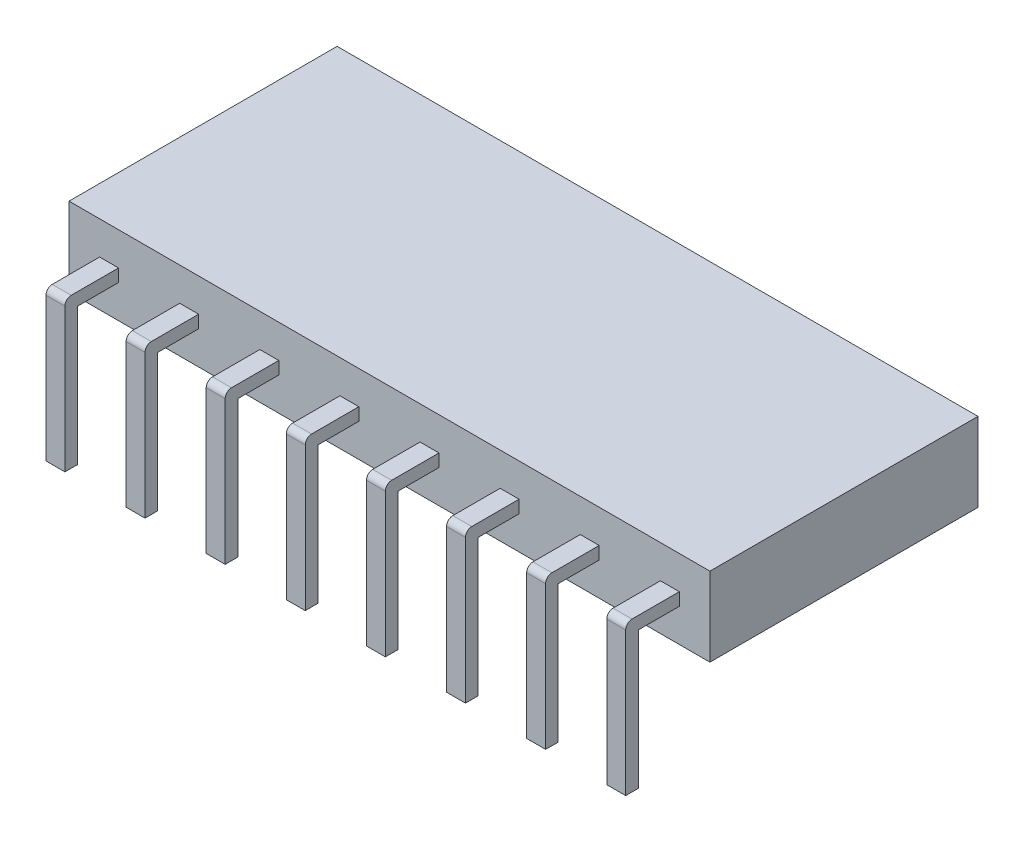
SolidWorks part; units mm, degrees
ref_plane "Front" through (0, 0, 0) normal (0, 0, 1) x (1, 0, 0)
ref_plane "Top" through (0, 0, 0) normal (0, 1, 0) x (1, 0, 0)
ref_plane "Right" through (0, 0, 0) normal (1, 0, 0) x (0, 0, -1)
sketch "Эскиз1" plane through (0, 0, 0) normal (0, 1, 0) x (1, 0, 0)
  line L1 (-10.16, 4.25) -> (10.16, 4.25)
  line L2 (-10.16, 4.25) -> (-10.16, -4.25)
  line L3 (-10.16, -4.25) -> (10.16, -4.25)
  line L4 (10.16, 4.25) -> (10.16, -4.25)
  line L5 (-10.16, 4.25) -> (10.16, -4.25) construction
  line L6 (-10.16, -4.25) -> (10.16, 4.25) construction
  point P0 (0, 0)
extrude "Бобышка-Вытянуть1" add sketch "Эскиз1" along normal blind 2.5
sketch "Эскиз2" plane through (0, 0, 4.25) normal (0, 0, 1) x (1, 0, 0)
  line L0 (-10.16, 1.25) -> (10.16, 1.25) construction
  line L1 (-10.16, 2.5) -> (-10.16, 0) construction
  line L2 (10.16, 2.5) -> (10.16, 0) construction
  line L3 (-6.65, 1.05) -> (-6.05, 1.05)
  line L4 (-9.19, 1.05) -> (-8.59, 1.05)
  line L5 (-9.19, 1.05) -> (-9.19, 1.45)
  line L6 (-9.19, 1.45) -> (-8.59, 1.45)
  line L7 (-8.59, 1.05) -> (-8.59, 1.45)
  line L8 (-9.19, 1.05) -> (-8.59, 1.45) construction
  line L9 (-9.19, 1.45) -> (-8.59, 1.05) construction
  line L10 (-6.65, 1.05) -> (-6.05, 1.45) construction
  line L11 (-6.65, 1.05) -> (-6.65, 1.45)
  line L12 (-6.65, 1.45) -> (-6.05, 1.45)
  line L13 (-6.65, 1.45) -> (-6.05, 1.05) construction
  line L14 (-6.05, 1.05) -> (-6.05, 1.45)
  line L15 (-4.11, 1.05) -> (-3.51, 1.05)
  line L16 (-4.11, 1.05) -> (-3.51, 1.45) construction
  line L17 (-4.11, 1.05) -> (-4.11, 1.45)
  line L18 (-4.11, 1.45) -> (-3.51, 1.45)
  line L19 (-4.11, 1.45) -> (-3.51, 1.05) construction
  line L20 (-3.51, 1.05) -> (-3.51, 1.45)
  line L21 (-1.57, 1.05) -> (-0.97, 1.05)
  line L22 (-1.57, 1.05) -> (-0.97, 1.45) construction
  line L23 (-1.57, 1.05) -> (-1.57, 1.45)
  line L24 (-1.57, 1.45) -> (-0.97, 1.45)
  line L25 (-1.57, 1.45) -> (-0.97, 1.05) construction
  line L26 (-0.97, 1.05) -> (-0.97, 1.45)
  line L27 (0.97, 1.05) -> (1.57, 1.05)
  line L28 (0.97, 1.05) -> (1.57, 1.45) construction
  line L29 (0.97, 1.05) -> (0.97, 1.45)
  line L30 (0.97, 1.45) -> (1.57, 1.45)
  line L31 (0.97, 1.45) -> (1.57, 1.05) construction
  line L32 (1.57, 1.05) -> (1.57, 1.45)
  line L33 (3.51, 1.05) -> (4.11, 1.05)
  line L34 (3.51, 1.05) -> (4.11, 1.45) construction
  line L35 (3.51, 1.05) -> (3.51, 1.45)
  line L36 (3.51, 1.45) -> (4.11, 1.45)
  line L37 (3.51, 1.45) -> (4.11, 1.05) construction
  line L38 (4.11, 1.05) -> (4.11, 1.45)
  line L39 (6.05, 1.05) -> (6.65, 1.05)
  line L40 (6.05, 1.05) -> (6.65, 1.45) construction
  line L41 (6.05, 1.05) -> (6.05, 1.45)
  line L42 (6.05, 1.45) -> (6.65, 1.45)
  line L43 (6.05, 1.45) -> (6.65, 1.05) construction
  line L44 (6.65, 1.05) -> (6.65, 1.45)
  line L45 (8.59, 1.05) -> (9.19, 1.05)
  line L46 (8.59, 1.05) -> (9.19, 1.45) construction
  line L47 (8.59, 1.05) -> (8.59, 1.45)
  line L48 (8.59, 1.45) -> (9.19, 1.45)
  line L49 (8.59, 1.45) -> (9.19, 1.05) construction
  line L50 (9.19, 1.05) -> (9.19, 1.45)
  dimension "D1" = 8
extrude "Бобышка-Вытянуть2" add sketch "Эскиз2" along normal blind 1.7
sketch "Эскиз3" plane through (0, 1.05, 0) normal (0, -1, 0) x (1, 0, 0)
  line L0 (-8.59, 5.95) -> (-8.59, 4.25) construction
  line L1 (-9.19, 5.95) -> (-8.59, 5.95)
  line L2 (-9.19, 5.95) -> (-9.19, 5.55)
  line L3 (-9.19, 5.55) -> (-8.59, 5.55)
  line L4 (-8.59, 5.95) -> (-8.59, 5.55)
  line L5 (-6.65, 5.95) -> (-6.05, 5.95)
  line L6 (-6.65, 5.95) -> (-6.65, 5.55)
  line L7 (-6.65, 5.55) -> (-6.05, 5.55)
  line L8 (-6.05, 5.95) -> (-6.05, 5.55)
  line L9 (-4.11, 5.95) -> (-3.51, 5.95)
  line L10 (-4.11, 5.95) -> (-4.11, 5.55)
  line L11 (-4.11, 5.55) -> (-3.51, 5.55)
  line L12 (-3.51, 5.95) -> (-3.51, 5.55)
  line L13 (-1.57, 5.95) -> (-0.97, 5.95)
  line L14 (-1.57, 5.95) -> (-1.57, 5.55)
  line L15 (-1.57, 5.55) -> (-0.97, 5.55)
  line L16 (-0.97, 5.95) -> (-0.97, 5.55)
  line L17 (0.97, 5.95) -> (1.57, 5.95)
  line L18 (0.97, 5.95) -> (0.97, 5.55)
  line L19 (0.97, 5.55) -> (1.57, 5.55)
  line L20 (1.57, 5.95) -> (1.57, 5.55)
  line L21 (3.51, 5.95) -> (4.11, 5.95)
  line L22 (3.51, 5.95) -> (3.51, 5.55)
  line L23 (3.51, 5.55) -> (4.11, 5.55)
  line L24 (4.11, 5.95) -> (4.11, 5.55)
  line L25 (6.05, 5.95) -> (6.65, 5.95)
  line L26 (6.05, 5.95) -> (6.05, 5.55)
  line L27 (6.05, 5.55) -> (6.65, 5.55)
  line L28 (6.65, 5.95) -> (6.65, 5.55)
  line L29 (8.59, 5.95) -> (9.19, 5.95)
  line L30 (8.59, 5.95) -> (8.59, 5.55)
  line L31 (8.59, 5.55) -> (9.19, 5.55)
  line L32 (9.19, 5.95) -> (9.19, 5.55)
  dimension "D1" = 8
extrude "Бобышка-Вытянуть3" add sketch "Эскиз3" along normal blind 4.35
fillet "Скругление1" radius 0.2 8 edges at (-8.89, 1.45, 5.95) (-6.35, 1.45, 5.95) (-3.81, 1.45, 5.95) (-1.27, 1.45, 5.95) (1.27, 1.45, 5.95) (3.81, 1.45, 5.95) (6.35, 1.45, 5.95) (8.89, 1.45, 5.95)
